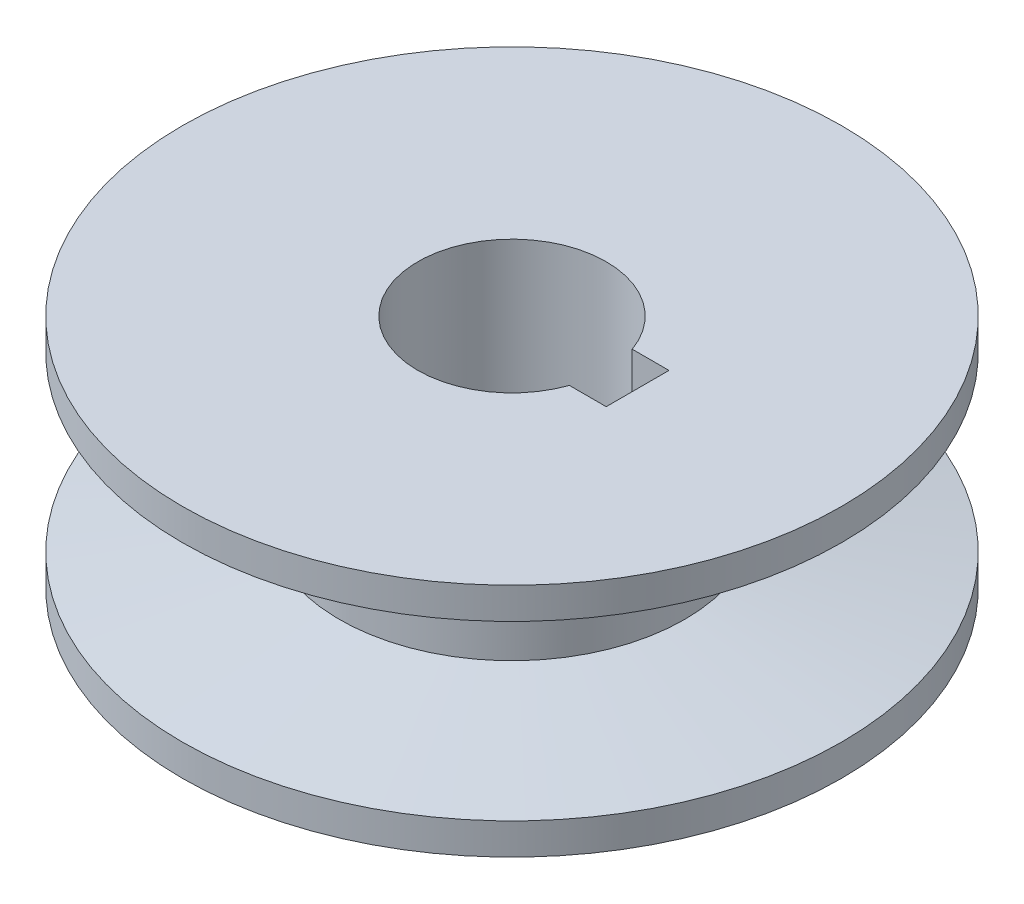
SolidWorks part; units mm, degrees
ref_plane "Front Plane" through (0, 0, 0) normal (0, 0, 1) x (1, 0, 0)
ref_plane "Top Plane" through (0, 0, 0) normal (0, 1, 0) x (1, 0, 0)
ref_plane "Right Plane" through (0, 0, 0) normal (1, 0, 0) x (0, 0, -1)
sketch "Sketch1" plane through (0, 0, 0) normal (0, 0, 1) x (1, 0, 0)
  line L0 (21, 5.5) -> (11, 3.7367)
  line L1 (6, -7.5) -> (21, -7.5)
  line L2 (6, -7.5) -> (6, 7.5)
  line L3 (6, 7.5) -> (21, 7.5)
  line L4 (21, -7.5) -> (21, -5.5)
  line L5 (11, 3.7367) -> (11, -3.7367)
  line L6 (11, -3.7367) -> (21, -5.5)
  line L7 (21, 5.5) -> (21, 7.5)
  line L8 (0, -1000.3568) -> (0, 1000.3568) construction
  point P4 (6, 0)
  point P11 (0, 0)
  dimension "D1" = 15
  dimension "D2" = 6
  dimension "D3" = 15
  dimension "D4" = 2
  dimension "D5" = 2
  dimension "D6" = 10
  dimension "D7" = 100
  dimension "D8" = 100
revolve "Revolve1" add sketch "Sketch1" angle 360 about L8
sketch "Sketch2" plane through (0, 7.5, 0) normal (0, 1, 0) x (1, 0, 0)
  line L1 (8, 2) -> (0, 2)
  line L2 (8, 2) -> (8, -2)
  line L3 (8, -2) -> (0, -2)
  line L4 (0, 2) -> (0, -2)
  point P4 (0, 0)
  dimension "D1" = 4
  dimension "D2" = 8
extrude "Cut-Extrude1" cut sketch "Sketch2" against normal up to surface (15 mm away) up to face at (21, -7.5, 0)
